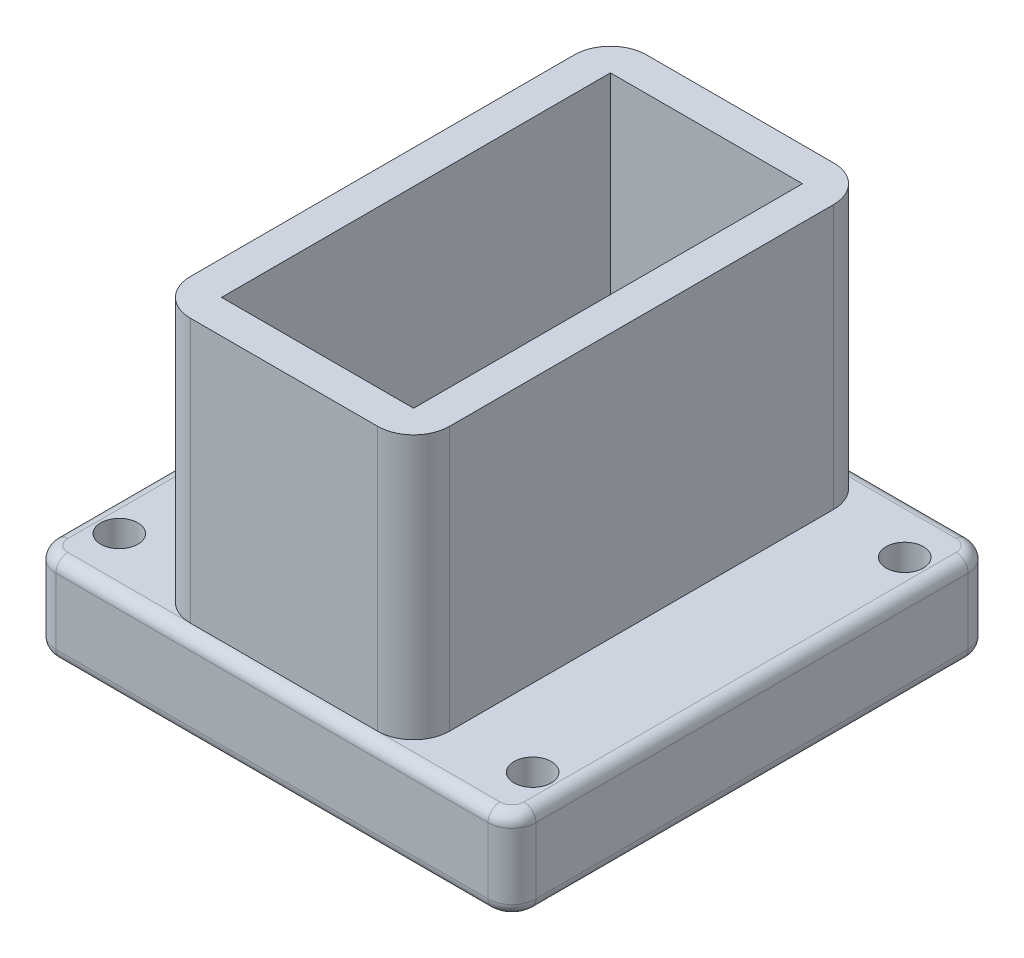
SolidWorks part; units mm, degrees
ref_plane "Front Plane" through (0, 0, 0) normal (0, 0, 1) x (1, 0, 0)
ref_plane "Top Plane" through (0, 0, 0) normal (0, 1, 0) x (1, 0, 0)
ref_plane "Right Plane" through (0, 0, 0) normal (1, 0, 0) x (0, 0, -1)
sketch "Sketch1" plane through (0, 0, 0) normal (0, 1, 0) x (1, 0, 0)
  line L1 (-18, 20) -> (18, 20)
  line L2 (-20, 18) -> (-20, -18)
  line L3 (-18, -20) -> (18, -20)
  line L4 (20, 18) -> (20, -18)
  line L5 (-20, 20) -> (20, -20) construction
  line L6 (-20, -20) -> (20, 20) construction
  line L7 (-17.22, -15.5) -> (17.22, -15.5) construction
  line L8 (-17.22, -15.5) -> (-17.22, 15.5) construction
  line L9 (-17.22, 15.5) -> (17.22, 15.5) construction
  line L10 (17.22, -15.5) -> (17.22, 15.5) construction
  line L11 (-17.22, -15.5) -> (17.22, 15.5) construction
  line L12 (-17.22, 15.5) -> (17.22, -15.5) construction
  arc A0 (18, -20) -> (20, -18) centre (18, -18) ccw
  arc A1 (20, 18) -> (18, 20) centre (18, 18) ccw
  arc A2 (-18, -20) -> (-20, -18) centre (-18, -18) cw
  arc A3 (-20, 18) -> (-18, 20) centre (-18, 18) cw
  circle A4 centre (-17.22, 15.5) radius 1.55
  circle A5 centre (-17.22, -15.5) radius 1.55
  circle A6 centre (17.22, 15.5) radius 1.55
  circle A7 centre (17.22, -15.5) radius 1.55
  point P0 (0, 0)
  point P18 (0, 0)
  dimension "D3" = 2
  dimension "D6" = 3.1
  dimension "D1" = 40
  dimension "D2" = 40
  dimension "D4" = 31
  dimension "D5" = 34.44
extrude "Boss-Extrude1" add sketch "Sketch1" along normal blind 7.5
fillet "Fillet2" radius 1 16 edges at (-19.4142, 0, 19.4142) (0, 0, 20) (19.4142, 0, 19.4142) (-20, 0, 0) (-19.4142, 0, -19.4142) (20, 0, 0) (19.4142, 0, -19.4142) (0, 0, -20) (19.4142, 7.5, 19.4142) (0, 7.5, 20) (-19.4142, 7.5, 19.4142) (20, 7.5, 0) (19.4142, 7.5, -19.4142) (0, 7.5, -20) (-19.4142, 7.5, -19.4142) (-20, 7.5, 0)
sketch "Sketch2" plane through (0, 7.5, 0) normal (0, 1, 0) x (1, 0, 0)
  circle A0 centre (0, 0) radius 7
  dimension "D1" = 14
extrude "Cut-Extrude1" cut sketch "Sketch2" against normal blind 10
sketch "Sketch3" plane through (0, 7.5, 0) normal (0, 1, 0) x (1, 0, 0)
  line L6 (18, 19) -> (-18, 19) construction
  line L13 (-10.8, 19) -> (10.8, 19)
  line L25 (-10.8, 19) -> (-10.8, -19)
  line L30 (-8, 16.2) -> (8, 16.2)
  line L31 (-8, 16.2) -> (-8, -16.2)
  line L32 (-8, -16.2) -> (8, -16.2)
  line L33 (8, 16.2) -> (8, -16.2)
  line L34 (-10.8, -19) -> (10.8, -19)
  line L35 (10.8, 19) -> (10.8, -19)
  line L36 (-18, -19) -> (18, -19) construction
  circle A0 centre (0, 0) radius 7 construction
  point P0 (0, 0)
  point P18 (0, 0)
  dimension "D3" = 2.8
  dimension "D6" = 2.8
  dimension "D2" = 8
  dimension "D1" = 8
  dimension "D4" = 2.8
  dimension "D5" = 2.8
  dimension "D7" = 38
  dimension "D8" = 21.6
  dimension "D9" = 16
  dimension "D10" = 32.4
extrude "Boss-Extrude9" add sketch "Sketch3" along normal blind 22
fillet "Fillet6" radius 3 4 edges at (10.8, 18.5, 19) (10.8, 18.5, -19) (-10.8, 18.5, 19) (-10.8, 18.5, -19)
